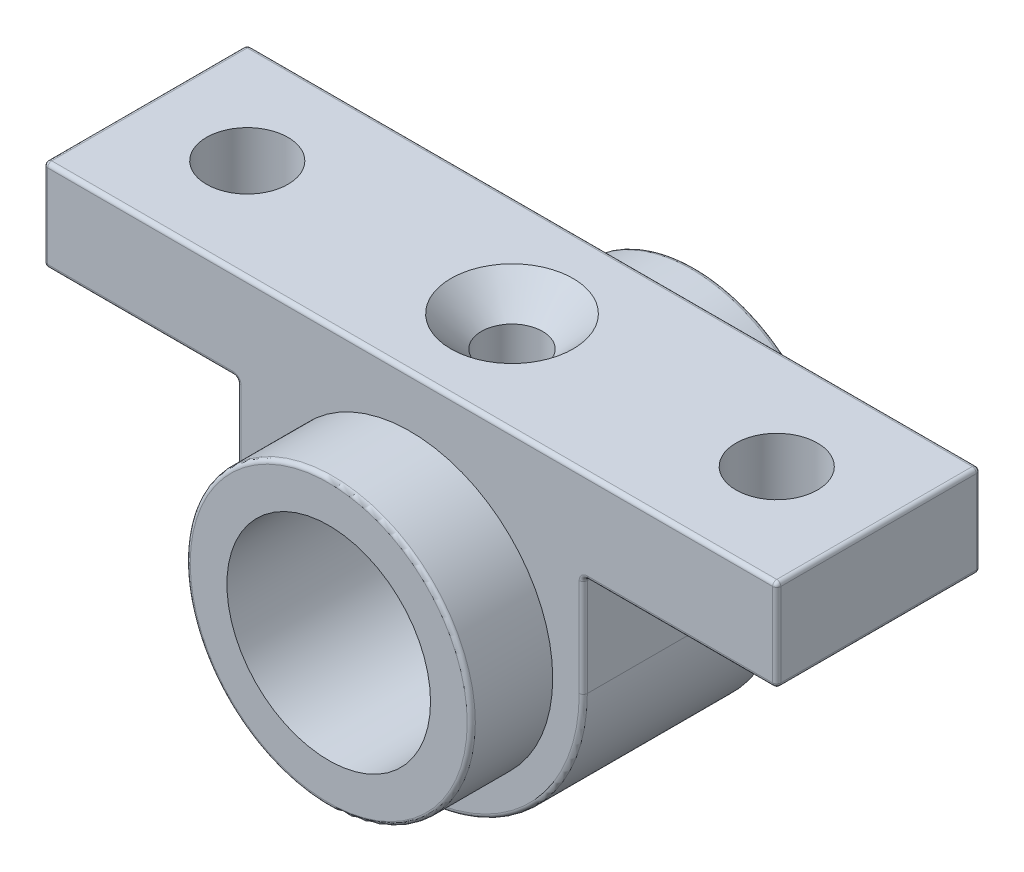
SolidWorks part; units mm, degrees
ref_plane "Front Plane" through (0, 0, 0) normal (0, 0, 1) x (1, 0, 0)
ref_plane "Top Plane" through (0, 0, 0) normal (0, 1, 0) x (1, 0, 0)
ref_plane "Right Plane" through (0, 0, 0) normal (1, 0, 0) x (0, 0, -1)
sketch "Sketch1" plane through (0, 0, 0) normal (0, 0, 1) x (1, 0, 0)
  line L8 (-8.5, 0) -> (-8.5, 5)
  line L9 (-8.5, 5) -> (-18, 5)
  line L10 (-18, 5) -> (-18, 9.5)
  line L11 (0, -55) -> (0, 55) construction
  line L12 (18, 5) -> (18, 9.5)
  line L13 (8.5, 5) -> (18, 5)
  line L14 (8.5, 0) -> (8.5, 5)
  line L15 (-18, 9.5) -> (18, 9.5)
  arc A2 (-8.5, 0) -> (8.5, 0) centre (0, 0) ccw
  circle A3 centre (0, 0) radius 5
  dimension "D1" = 10
  dimension "D2" = 8.5
  dimension "D3" = 18
  dimension "D4" = 9.5
extrude "Boss-Extrude1" add sketch "Sketch1" along normal mid plane 10
sketch "Sketch2" plane through (0, 0, 5) normal (0, 0, 1) x (1, 0, 0)
  circle A0 centre (0, 0) radius 7
  dimension "D1" = 14
extrude "Boss-Extrude2" add sketch "Sketch2" along normal blind 4
sketch "Sketch3" plane through (0, 0, 9) normal (0, 0, 1) x (1, 0, 0)
  circle A0 centre (0, 0) radius 5
  circle A1 centre (0, 0) radius 7 construction
  dimension "D1" = 10
extrude "Cut-Extrude1" cut sketch "Sketch3" against normal blind 4
mirror "Mirror1" about plane through (0, 0, 0) normal (0, 0, 1) of "Cut-Extrude1", "Boss-Extrude2"
sketch "Sketch5" plane through (0, 9.5, 0) normal (0, 1, 0) x (1, 0, 0)
  line L0 (-18, -5) -> (-18, 5) construction
  line L1 (18, -5) -> (18, 5) construction
  line L2 (18, 5) -> (-18, 5) construction
  circle A0 centre (-13, 0) radius 2
  circle A1 centre (13, 0) radius 2
  dimension "D1" = 5
  dimension "D2" = 5
  dimension "D3" = 4
  dimension "D4" = 5
extrude "Cut-Extrude2" cut sketch "Sketch5" against normal through all
hole_wizard "CSK for M3 Flat Head Machine Screw1" positions "Sketch6" profile "Sketch7" countersink size "M3" standard "ANSI Metric"
sketch "Sketch6" plane through (0, 9.5, 0) normal (0, 1, 0) x (1, 0, 0)
  point P0 (0, 0)
sketch "Sketch7" plane through (0, 9.5, 0) normal (1, 0, 0) x (0, 0, 1)
  line L0 (0, 0) -> (0, 9)
  line L1 (0, 9) -> (1.5, 8.0987)
  line L2 (1.5, 8.0987) -> (1.5, 1.5)
  line L3 (1.5, 1.5) -> (3, 0)
  line L5 (3, 0) -> (0, 0)
  line L6 (-1.5, 1.5) -> (-3, 0) construction
  line L10 (0, 9) -> (-1.5, 8.0987) construction
  line L11 (0, -6.35) -> (0, 107.95) construction
  dimension "Hole Dia." = 3
  dimension "Hole Depth" = 9
  dimension "Near C'Sink Dia." = 6
  dimension "Near C'Sink Angle" = 90
  dimension "Drill Angle" = 118
fillet "Fillet1" radius 0.2 24 edges at (18, 7.25, -5) (18, 7.25, 5) (-18, 7.25, -5) (-18, 7.25, 5) (0, -8.5, -5) (0, -8.5, 5) (8.5, 2.5, -5) (8.5, 2.5, 5) (13.25, 5, -5) (13.25, 5, 5) (0, 9.5, -5) (0, 9.5, 5) (-13.25, 5, -5) (-13.25, 5, 5) (-8.5, 2.5, -5) (-8.5, 2.5, 5) (-8.5, 5, 0) (-18, 5, 0) (-18, 9.5, 0) (18, 9.5, 0) (18, 5, 0) (8.5, 5, 0) (7, 0, -9) (7, 0, 9)
